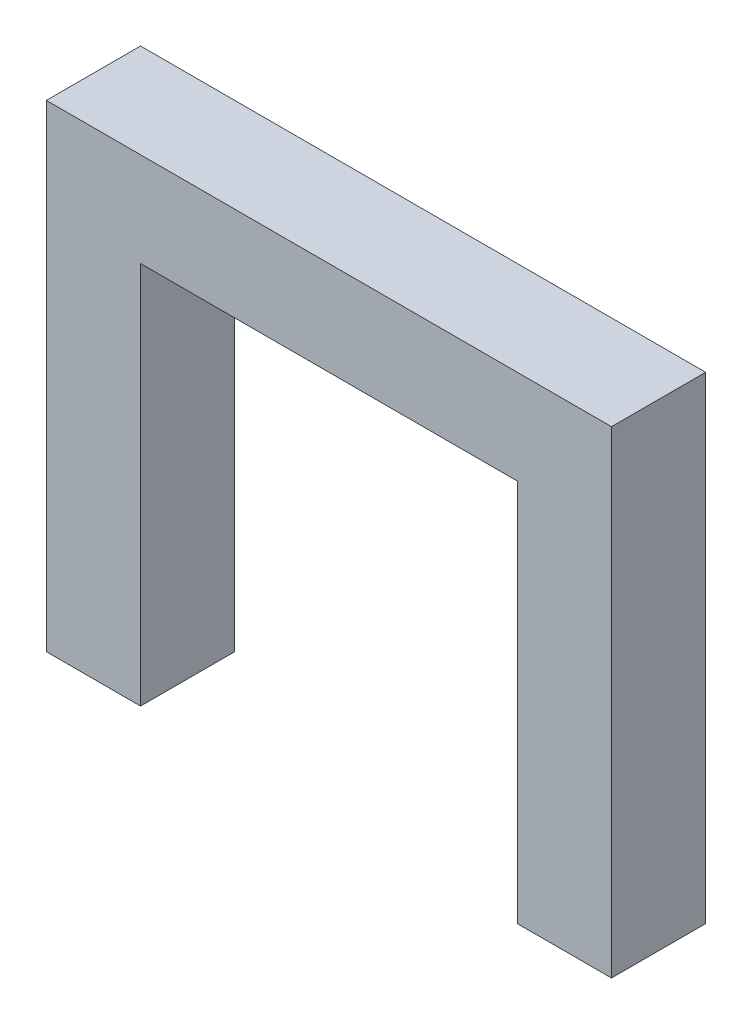
SolidWorks part; units mm, degrees
ref_plane "Front Plane" through (0, 0, 0) normal (0, 0, 1) x (1, 0, 0)
ref_plane "Top Plane" through (0, 0, 0) normal (0, 1, 0) x (1, 0, 0)
ref_plane "Right Plane" through (0, 0, 0) normal (1, 0, 0) x (0, 0, -1)
sketch "Sketch1" plane through (0, 0, 0) normal (0, 0, 1) x (1, 0, 0)
  line L0 (-28.4519, -52.7608) -> (-28.4519, 48.6192)
  line L1 (-28.4519, 48.6192) -> (91.5481, 48.6192)
  line L2 (91.5481, 48.6192) -> (91.5481, -52.7608)
  line L3 (91.5481, -52.7608) -> (71.5481, -52.7608)
  line L4 (71.5481, -52.7608) -> (71.5481, 28.6192)
  line L5 (71.5481, 28.6192) -> (-8.4519, 28.6192)
  line L6 (-8.4519, 28.6192) -> (-8.4519, -52.7608)
  line L7 (-8.4519, -52.7608) -> (-28.4519, -52.7608)
  line L8 (-8.4519, 28.6192) -> (-28.4519, 28.6192)
  line L9 (71.5481, 28.6192) -> (91.5481, 28.6192)
  dimension "D1" = 101.38
  dimension "D2" = 120
  dimension "D3" = 20
  dimension "D4" = 20
  dimension "D5" = 20
  dimension "D6" = 101.38
extrude "Boss-Extrude2" add sketch "Sketch1" along normal blind 20 contours L6 L8 L0 L7 | L5 L9 L2 L1 L0 L8 | L9 L4 L3 L2
